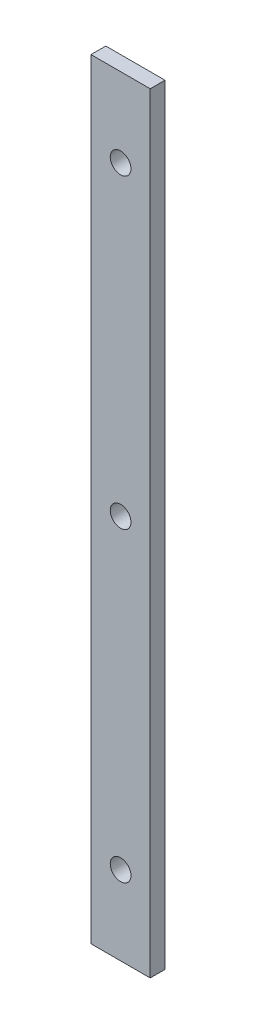
SolidWorks part; units mm, degrees
ref_plane "Front Plane" through (0, 0, 0) normal (0, 0, 1) x (1, 0, 0)
ref_plane "Top Plane" through (0, 0, 0) normal (0, 1, 0) x (1, 0, 0)
ref_plane "Right Plane" through (0, 0, 0) normal (1, 0, 0) x (0, 0, -1)
sketch "Sketch1" plane through (0, 0, 0) normal (0, 0, 1) x (1, 0, 0)
  line L0 (82.55, 70) -> (82.55, 80) construction
  line L1 (82.55, 78) -> (70.55, 78)
  line L2 (82.55, 78) -> (82.55, -78)
  line L3 (82.55, -78) -> (70.55, -78)
  line L4 (70.55, 78) -> (70.55, -78)
  line L5 (82.55, 68) -> (-82.55, 68) construction
  line L6 (-82.55, -68) -> (82.55, -68) construction
  dimension "D1" = 10
  dimension "D2" = 10
  dimension "D3" = 12
extrude "Boss-Extrude1" add sketch "Sketch1" along normal blind 3
sketch "Sketch2" plane through (0, 0, 0) normal (0, 0, -1) x (-1, 0, 0)
  line L0 (-70.55, 0) -> (-3.3499, 0) construction
  line L1 (-70.55, 78) -> (-70.55, -78) construction
  line L2 (82.55, -68) -> (-82.55, -68) construction
  circle A0 centre (-76.55, -62) radius 2.1
  circle A1 centre (-76.55, 0) radius 2.1
  circle A2 centre (-76.55, 62) radius 2.1
  dimension "D1" = 3
  dimension "D2" = 6
  dimension "D3" = 6
  dimension "D4" = 4.2
extrude "Cut-Extrude1" cut sketch "Sketch2" against normal up to next
